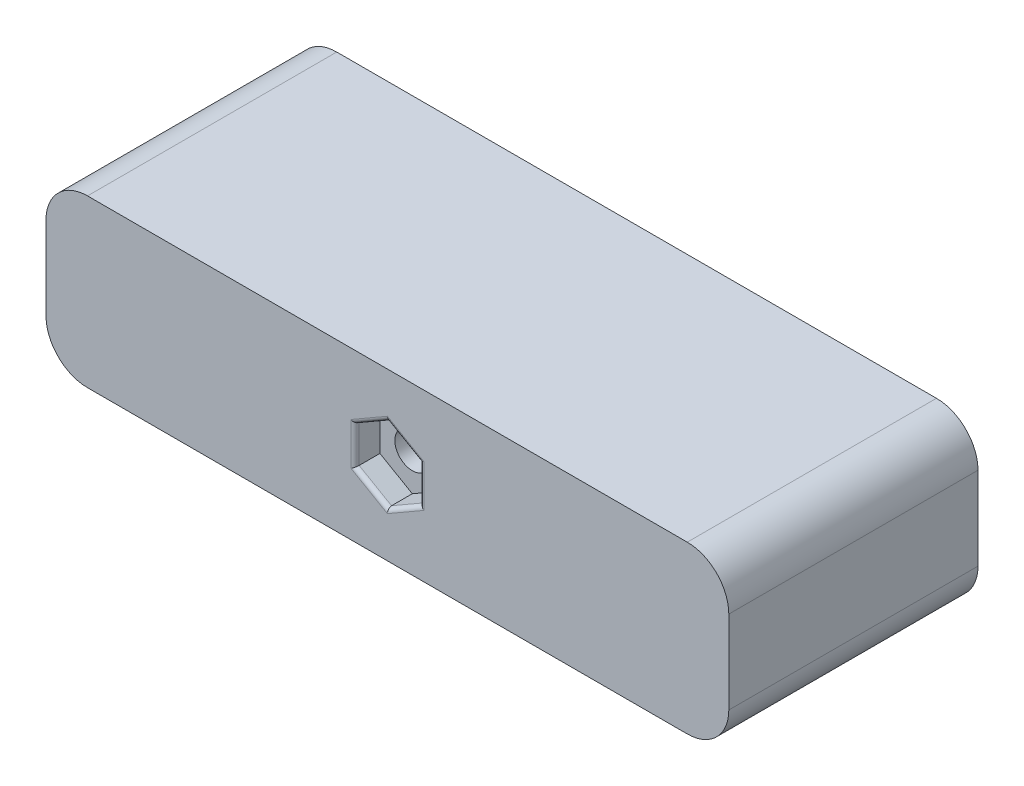
SolidWorks part; units mm, degrees
material "PVC 0.007 plastifié"
ref_plane "Plan de face" through (0, 0, 0) normal (0, 0, 1) x (1, 0, 0)
ref_plane "Plan de dessus" through (0, 0, 0) normal (0, 1, 0) x (1, 0, 0)
ref_plane "Plan de droite" through (0, 0, 0) normal (1, 0, 0) x (0, 0, -1)
sketch "Esquisse1" plane through (0, 0, 0) normal (0, 0, 1) x (1, 0, 0)
  line L1 (0, 0) -> (-82.2, 0)
  line L2 (0, 0) -> (0, 20)
  line L3 (0, 20) -> (-82.2, 20)
  line L4 (-82.2, 0) -> (-82.2, 20)
  dimension "D1" = 82.2
  dimension "D2" = 20
extrude "Boss.-Extru.1" add sketch "Esquisse1" along normal blind 30
sketch "Esquisse4" plane through (0, 0, 30) normal (0, 0, 1) x (1, 0, 0)
  line L0 (0, 20) -> (-82.2, 20) construction
  line L1 (-82.2, 20) -> (-82.2, 0) construction
  point P0 (-41.1, 20)
  point P1 (-82.2, 10)
sketch "Esquisse2" plane through (0, 0, 30) normal (0, 0, 1) x (1, 0, 0)
  line L0 (0, 0) -> (0, 20) construction
  line L1 (-41.1, 5.4967) -> (-37.2, 7.7483)
  line L2 (-37.2, 7.7483) -> (-37.2, 12.2517)
  line L3 (-37.2, 12.2517) -> (-41.1, 14.5033)
  line L4 (-41.1, 14.5033) -> (-45, 12.2517)
  line L5 (-45, 12.2517) -> (-45, 7.7483)
  line L6 (-45, 7.7483) -> (-41.1, 5.4967)
  circle A0 centre (-41.1, 10) radius 3.9 construction
  dimension "D1" = 7.8
extrude "Enlèv. mat.-Extru.1" cut sketch "Esquisse2" against normal blind 3
fillet "Congé1" radius 5 4 edges at (-82.2, 0, 15) (-82.2, 20, 15) (0, 0, 15) (0, 20, 15)
sketch "Esquisse3" plane through (0, 0, 30) normal (0, 0, 1) x (1, 0, 0)
  line L0 (0, 5) -> (0, 15) construction
  line L1 (-82.2, 15) -> (-82.2, 5) construction
  circle A0 centre (-10, 9.9745) radius 10
  circle A1 centre (-72.2, 9.9745) radius 9.9745
  dimension "D1" = 20
  dimension "D2" = 10
  dimension "D3" = 10
fillet "Congé2" radius 0.5 6 edges at (-45, 10, 30) (-43.05, 6.6225, 30) (-39.15, 6.6225, 30) (-37.2, 10, 30) (-39.15, 13.3775, 30) (-43.05, 13.3775, 30)
sketch "Esquisse8" plane through (0, 0, 0) normal (0, 0, 1) x (1, 0, 0)
  line L0 (0, 5) -> (0, 15) construction
  circle A0 centre (-41.1, 10) radius 2.1038
  dimension "D1" = 10
  dimension "D2" = 41.1
extrude "Enlèv. mat.-Extru.3" cut sketch "Esquisse8" along normal through all
